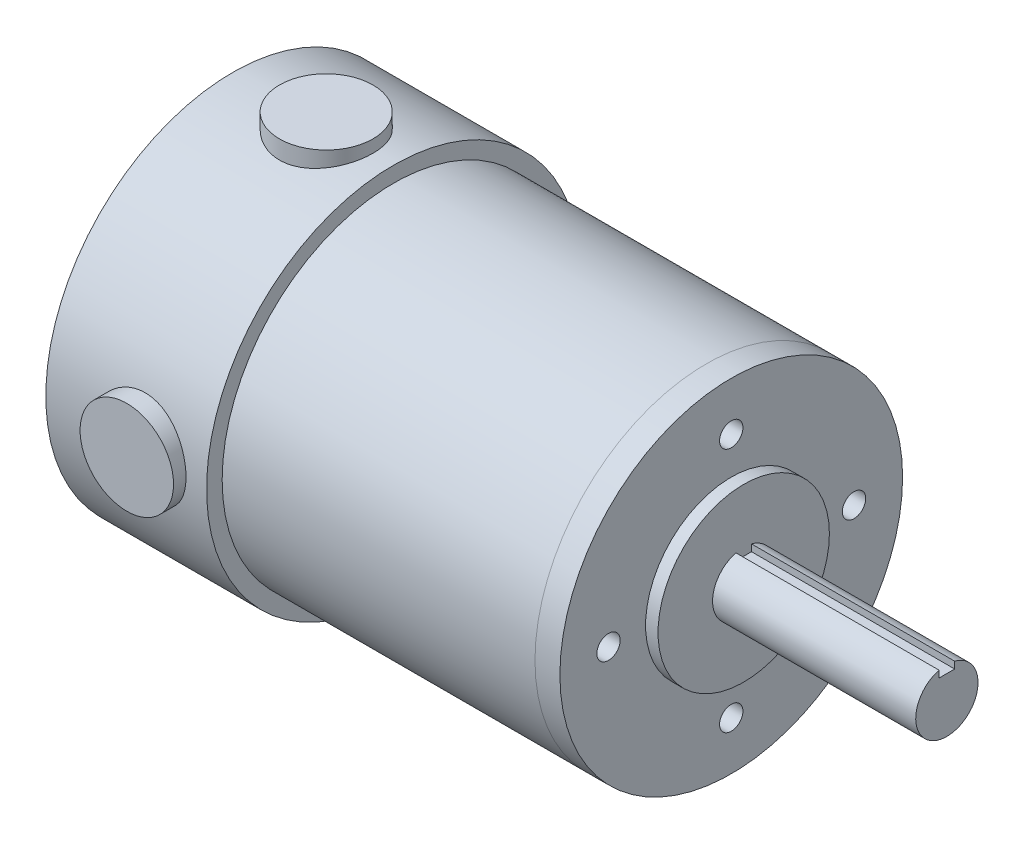
SolidWorks part; units mm, degrees
ref_plane "Front Plane" through (0, 0, 0) normal (0, 0, 1) x (1, 0, 0)
ref_plane "Top Plane" through (0, 0, 0) normal (0, 1, 0) x (1, 0, 0)
ref_plane "Right Plane" through (0, 0, 0) normal (1, 0, 0) x (0, 0, -1)
sketch "Sketch1" plane through (0, 0, 0) normal (1, 0, 0) x (0, 0, -1)
  circle A0 centre (0, 0) radius 38.1
  dimension "D1" = 76.2
extrude "Extrude1" add sketch "Sketch1" along normal blind 32.766
sketch "Sketch2" plane through (32.766, 0, 0) normal (1, 0, 0) x (0, 0, -1)
  circle A0 centre (0, 0) radius 34.925
  dimension "D1" = 69.85
sketch "Sketch5" plane through (0, 0, 0) normal (-1, 0, 0) x (0, 0, 1)
  circle A0 centre (0, 0) radius 6.35
  dimension "D1" = 12.7
extrude "Extrude5" add sketch "Sketch5" along normal blind 18.288
extrude "Extrude6" add sketch "Sketch2" along normal blind 63.754
sketch "Sketch6" plane through (96.52, 0, 0) normal (1, 0, 0) x (0, 0, -1)
  circle A0 centre (0, 0) radius 34.925
  dimension "D1" = 69.85
extrude "Extrude7" add sketch "Sketch6" along normal blind 5.08 separate body
sketch "Sketch7" plane through (101.6, 0, 0) normal (1, 0, 0) x (0, 0, -1)
  circle A0 centre (0, 0) radius 17.4625
  dimension "D1" = 34.925
extrude "Extrude8" add sketch "Sketch7" along normal blind 2.54
sketch "Sketch8" plane through (101.6, 0, 0) normal (1, 0, 0) x (0, 0, -1)
  circle A0 centre (0, 0) radius 6.35
  dimension "D1" = 12.7
extrude "Extrude9" add sketch "Sketch8" along normal blind 43.942
sketch "Sketch9" plane through (145.542, 0, 0) normal (1, 0, 0) x (0, 0, -1)
  line L1 (-1.5875, 4.7625) -> (1.5875, 4.7625)
  line L2 (-1.5875, 4.7625) -> (-1.5875, 7.9375)
  line L3 (-1.5875, 7.9375) -> (1.5875, 7.9375)
  line L4 (1.5875, 4.7625) -> (1.5875, 7.9375)
  dimension "D1" = 3.175
  dimension "D2" = 3.175
  dimension "D3" = 4.7625
  dimension "D4" = 1.5875
extrude "Cut-Extrude1" cut sketch "Sketch9" against normal up to surface (41.402 mm away) up to face at (104.14, 0, -17.4625)
sketch "Sketch10" plane through (-18.288, 0, 0) normal (-1, 0, 0) x (0, 0, 1)
  line L1 (-1.5875, 4.7625) -> (1.5875, 4.7625)
  line L2 (-1.5875, 4.7625) -> (-1.5875, 7.9375)
  line L3 (-1.5875, 7.9375) -> (1.5875, 7.9375)
  line L4 (1.5875, 4.7625) -> (1.5875, 7.9375)
  dimension "D1" = 3.175
  dimension "D2" = 3.175
  dimension "D3" = 4.7625
  dimension "D4" = 1.5875
extrude "Cut-Extrude2" cut sketch "Sketch10" against normal up to surface (18.288 mm away) up to face at (0, 0, -38.1)
sketch "Sketch11" plane through (0, 0, 0) normal (0, 1, 0) x (1, 0, 0)
  line L0 (0, 38.1) -> (0, -38.1) construction
  circle A0 centre (19.05, 0) radius 9.525
  dimension "D1" = 19.05
  dimension "D2" = 19.05
extrude "Extrude10" add sketch "Sketch11" along normal mid plane 81.28
sketch "Sketch12" plane through (0, 0, 0) normal (0, 0, 1) x (1, 0, 0)
  circle A0 centre (19.05, 0) radius 9.525
  dimension "D1" = 19.05
  dimension "D2" = 19.05
extrude "Extrude11" add sketch "Sketch12" along normal mid plane 81.28
sketch "Sketch13" plane through (101.6, 0, 0) normal (1, 0, 0) x (0, 0, -1)
  circle A0 centre (25.019, 0) radius 2.3813
  circle A1 centre (0, 25.019) radius 2.3813
  circle A2 centre (-25.019, 0) radius 2.3813
  circle A3 centre (0, -25.019) radius 2.3813
  dimension "D1" = 4.7625
  dimension "D2" = 4.7625
  dimension "D3" = 4.7625
  dimension "D4" = 4.7625
  dimension "D5" = 25.019
  dimension "D6" = 25.019
  dimension "D7" = 25.019
  dimension "D8" = 25.019
extrude "Cut-Extrude3" cut sketch "Sketch13" against normal blind 9.525
